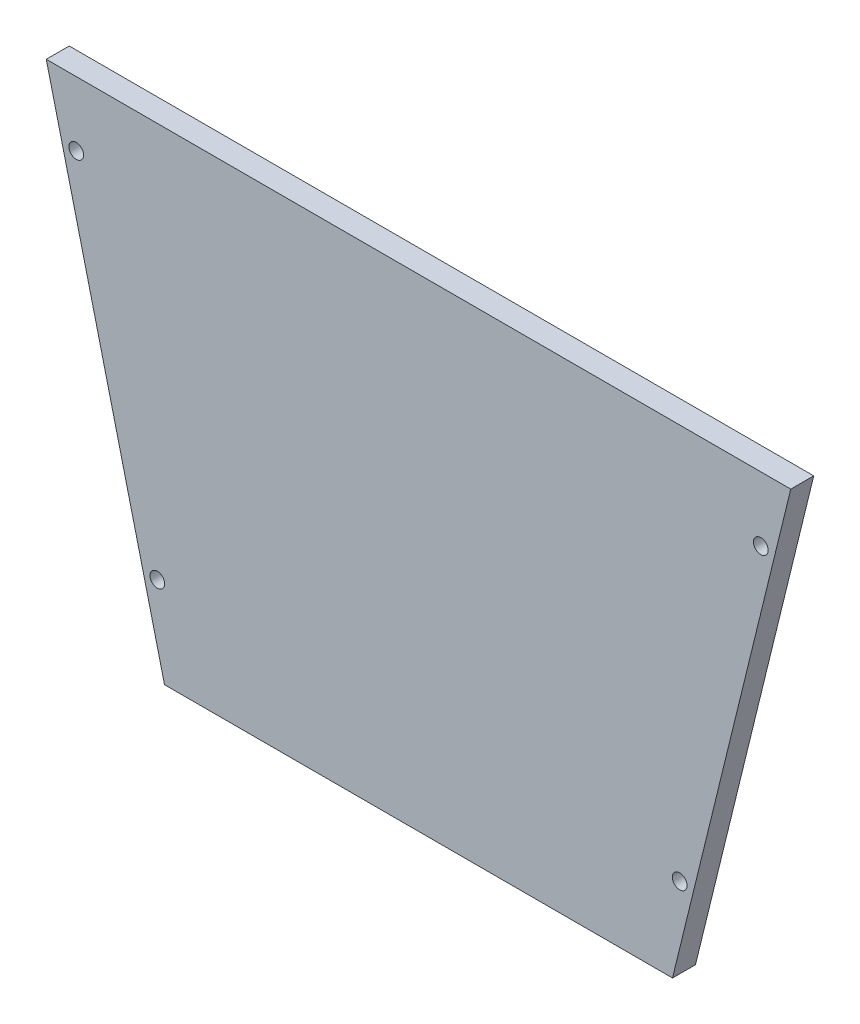
SolidWorks part; units mm, degrees
ref_plane "Front" through (0, 0, 0) normal (0, 0, 1) x (1, 0, 0)
ref_plane "Top" through (0, 0, 0) normal (0, 1, 0) x (1, 0, 0)
ref_plane "Right" through (0, 0, 0) normal (1, 0, 0) x (0, 0, -1)
sketch "草图2" plane through (0, 0, 0) normal (0, 0, 1) x (1, 0, 0)
  line L0 (0, 0) -> (112.5, 0)
  line L1 (112.5, 0) -> (137.5, 102)
  line L2 (137.5, 102) -> (-25, 102)
  line L3 (-25, 102) -> (0, 0)
  dimension "D1" = 112.5
  dimension "D2" = 102
  dimension "D3" = 162.5
  dimension "D4" = 25
extrude "凸台-拉伸2" add sketch "草图2" along normal blind 5
sketch "草图3" plane through (0, 0, 5) normal (0, 0, 1) x (1, 0, 0)
  line L0 (137.5, 102) -> (-25, 102) construction
  line L1 (-25, 102) -> (0, 0) construction
  line L2 (0, 0) -> (112.5, 0) construction
  line L3 (112.5, 0) -> (137.5, 102) construction
  circle A0 centre (-18.2347, 87) radius 1.6
  circle A1 centre (113.0877, 15) radius 1.6
  circle A2 centre (-0.5877, 15) radius 1.6
  circle A3 centre (130.7347, 87) radius 1.6
  dimension "D1" = 15
  dimension "D2" = 3
  dimension "D3" = 15
  dimension "D4" = 3
  dimension "D5" = 15
  dimension "D6" = 3
  dimension "D7" = 15
  dimension "D8" = 3
extrude "切除-拉伸1" cut sketch "草图3" against normal through all
sketch "草图4" plane through (0, 0, 5) normal (0, 0, 1) x (1, 0, 0)
  line L1 (-25, 102) -> (139.707, 102)
  line L2 (-25, 102) -> (-25, 101)
  line L3 (-25, 101) -> (139.707, 101)
  line L4 (139.707, 102) -> (139.707, 101)
  dimension "D1" = 1
extrude "切除-拉伸2" cut sketch "草图4" against normal through all
sketch "草图5" plane through (0, 0, 5) normal (0, 0, 1) x (1, 0, 0)
  line L0 (0, 0) -> (0.9804, -4)
  line L1 (0.9804, -4) -> (111.5196, -4)
  line L2 (111.5196, -4) -> (112.5, 0)
  line L3 (112.5, 0) -> (0, 0)
  line L4 (-24.7549, 101) -> (0, 0) construction
  line L5 (112.5, 0) -> (137.2549, 101) construction
  dimension "D1" = 180
  dimension "D2" = 180
  dimension "D3" = 4
  dimension "D4" = 4
extrude "凸台-拉伸3" add sketch "草图5" against normal blind 5
